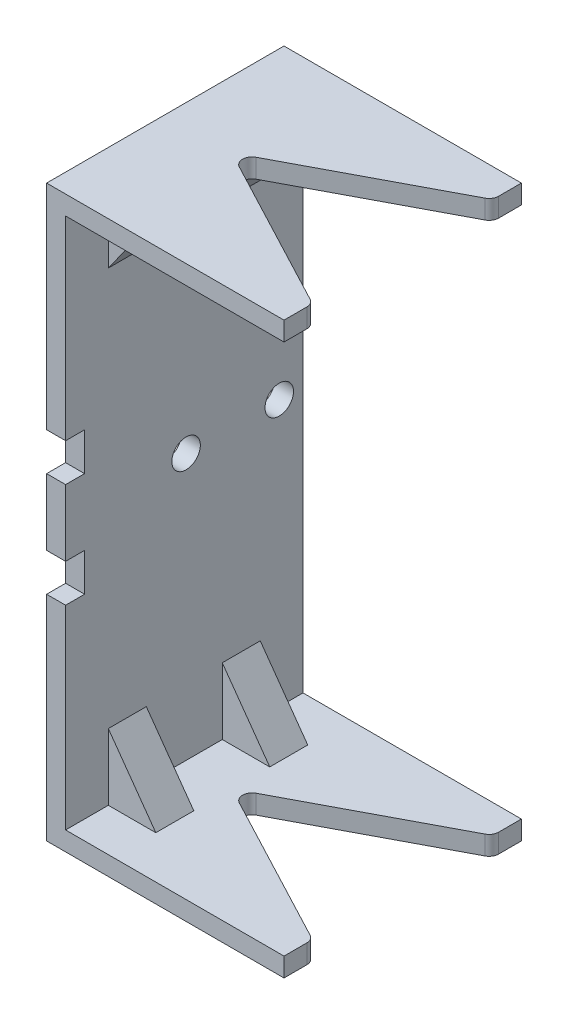
SolidWorks part; units mm, degrees
material "ABS"
ref_plane "Front Plane" through (0, 0, 0) normal (0, 0, 1) x (1, 0, 0)
ref_plane "Top Plane" through (0, 0, 0) normal (0, 1, 0) x (1, 0, 0)
ref_plane "Right Plane" through (0, 0, 0) normal (1, 0, 0) x (0, 0, -1)
sketch "Sketch1" plane through (0, 0, 0) normal (0, 0, 1) x (1, 0, 0)
  line L0 (0, 0) -> (0, 60)
  line L1 (0, 60) -> (25, 60)
  line L2 (25, 60) -> (25, 58)
  line L3 (25, 58) -> (2, 58)
  line L4 (2, 58) -> (2, 2)
  line L5 (2, 2) -> (25, 2)
  line L6 (25, 2) -> (25, 0)
  line L7 (25, 0) -> (0, 0)
  dimension "D1" = 60
  dimension "D2" = 25
  dimension "D3" = 25
  dimension "D4" = 2
  dimension "D5" = 2
  dimension "D6" = 2
extrude "Boss-Extrude2" add sketch "Sketch1" along normal mid plane 25
sketch "Sketch6" plane through (0, 60, 0) normal (0, 1, 0) x (1, 0, 0)
  line L0 (7, 14.3715) -> (7, -16.1158) construction
  line L1 (0, -12.5) -> (0, 12.5) construction
  line L2 (-4.4121, 0) -> (33.5832, 0) construction
  line L5 (7, 0) -> (25, 9.5)
  line L6 (25, -12.5) -> (25, 12.5) construction
  line L7 (25, 9.5) -> (25, -9.5)
  line L8 (25, -9.5) -> (7, 0)
  line L9 (25, -12.5) -> (0, -12.5) construction
  line L10 (25, 12.5) -> (0, 12.5) construction
  point P11 (7, 0)
  dimension "D1" = 7
  dimension "D2" = 3
  dimension "D3" = 3
extrude "Cut-Extrude1" cut sketch "Sketch6" against normal through all
fillet "Fillet1" radius 1 6 edges at (7, 1, 0) (7, 59, 0) (25, 1, -9.5) (25, 1, 9.5) (25, 59, -9.5) (25, 59, 9.5)
sketch "Sketch7" plane through (2, 0, 0) normal (1, 0, 0) x (0, 0, -1)
  line L0 (-20.0973, 30) -> (20.4765, 30) construction
  line L1 (0, 68.1136) -> (0, -17.5055) construction
  circle A0 centre (0.1896, 30) radius 1.5
  circle A1 centre (10, 30) radius 1.5
  point P5 (0, 30)
  point P6 (10, 30)
  dimension "D2" = 3
  dimension "D4" = 3
  dimension "D1" = 30
  dimension "D3" = 10
extrude "Cut-Extrude2" cut sketch "Sketch7" against normal blind 10
sketch "Sketch13" plane through (0, 0, 0) normal (0, 0, 1) x (1, 0, 0)
  line L0 (2, 58) -> (7, 58)
  line L1 (2, 58) -> (2, 51)
  line L2 (2, 2) -> (2, 58) construction
  line L3 (2, 58) -> (25, 58) construction
  line L4 (7, 2) -> (2, 2)
  line L5 (25, 2) -> (2, 2) construction
  line L6 (2, 2) -> (2, 9)
  line L7 (2, 9) -> (7, 2)
  line L8 (7, 58) -> (2, 51)
  dimension "D1" = 7
  dimension "D2" = 5
  dimension "D3" = 5
  dimension "D4" = 7
extrude "Boss-Extrude8" add sketch "Sketch13" along normal mid plane 16
sketch "Sketch14" plane through (0, 0, 0) normal (0, 0, 1) x (1, 0, 0)
  line L0 (2, 2) -> (2, 9)
  line L1 (2, 9) -> (7, 2)
  line L2 (7, 2) -> (2, 2)
  line L3 (2, 58) -> (7, 58)
  line L4 (7, 58) -> (2, 51)
  line L5 (2, 51) -> (2, 58)
extrude "Cut-Extrude4" cut sketch "Sketch14" against normal mid plane 8
sketch "Sketch15" plane through (2, 0, 0) normal (1, 0, 0) x (0, 0, -1)
  line L0 (-12.5, 2) -> (-12.5, 58) construction
  line L1 (-12.5, 33.5) -> (-10.5, 33.5)
  line L3 (-12.5, 26.5) -> (-10.5, 26.5)
  line L6 (-10.5, 33.5) -> (-10.5, 37.5)
  line L7 (-10.5, 37.5) -> (-12.5, 37.5)
  line L8 (-12.5, 37.5) -> (-12.5, 33.5)
  line L9 (-10.5, 26.5) -> (-10.5, 22.5)
  line L10 (-10.5, 22.5) -> (-12.5, 22.5)
  line L11 (-12.5, 22.5) -> (-12.5, 26.5)
  dimension "D1" = 7
  dimension "D2" = 2
  dimension "D4" = 4
  dimension "D5" = 4
extrude "Cut-Extrude5" cut sketch "Sketch15" against normal blind 2
